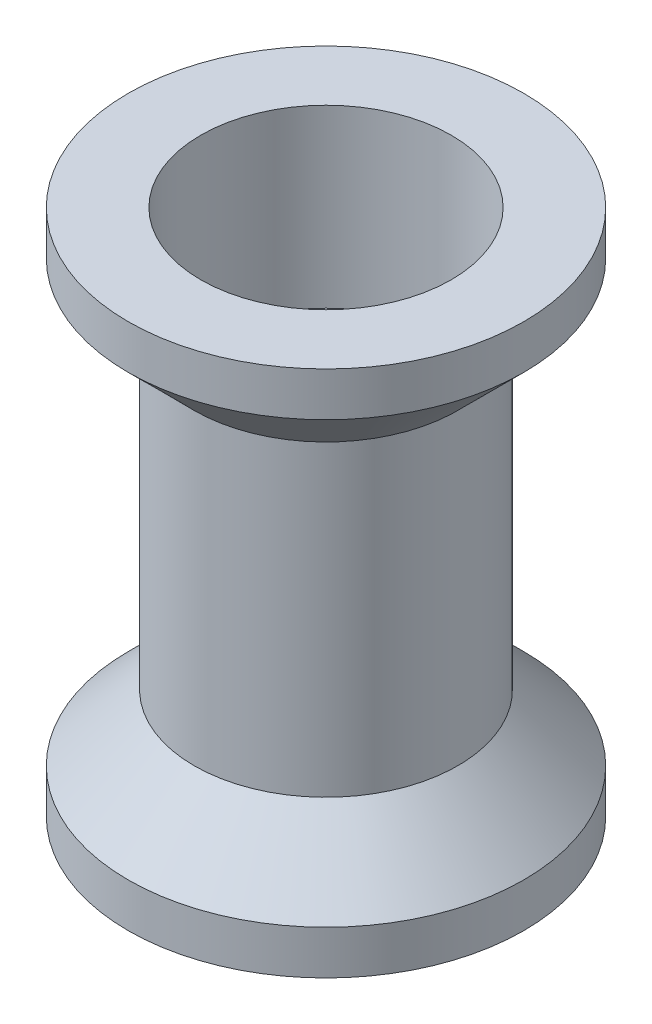
SolidWorks part; units mm, degrees
ref_plane "Front Plane" through (0, 0, 0) normal (0, 0, 1) x (1, 0, 0)
ref_plane "Top Plane" through (0, 0, 0) normal (0, 1, 0) x (1, 0, 0)
ref_plane "Right Plane" through (0, 0, 0) normal (1, 0, 0) x (0, 0, -1)
sketch "Sketch1" plane through (0, 0, 0) normal (0, 1, 0) x (1, 0, 0)
  line L0 (0, 0) -> (0, 2.5) construction
  line L1 (0, 2.5) -> (0, -2.5) construction
  line L2 (0, -2.5) -> (2.5, 0) construction
  line L3 (2.5, 0) -> (-2.5, 0) construction
  line L4 (-2.5, 0) -> (0, 2.5) construction
  line L5 (0, 2.5) -> (2.5, 0) construction
  line L6 (-2.5, 0) -> (0, -2.5) construction
  line L7 (0, 0) -> (-1.7678, 1.7678) construction
  line L8 (-1.7678, 1.7678) -> (-1.7678, -1.7678) construction
  line L9 (-1.7678, -1.7678) -> (1.7678, -1.7678) construction
  line L10 (1.7678, -1.7678) -> (1.7678, 1.7678) construction
  line L11 (1.7678, 1.7678) -> (-1.7678, 1.7678)
  arc A0 (-1.7678, 1.7678) -> (1.7678, 1.7678) centre (0, 0) ccw
  circle A1 centre (0, 0) radius 22.5
  dimension "D1" = 5
  dimension "D2" = 45
  dimension "D3" = 3.5355
extrude "Boss-Extrude1" add sketch "Sketch1" along normal blind 60
sketch "Sketch2" plane through (0, 60, 0) normal (0, 1, 0) x (1, 0, 0)
  circle A0 centre (0, 0) radius 14.25
  dimension "D1" = 28.5
extrude "Cut-Extrude1" cut sketch "Sketch2" against normal blind 20
sketch "Sketch4" plane through (0, 0, 0) normal (0, 0, 1) x (1, 0, 0)
  line L0 (0, 0) -> (22.5, 0) construction
  line L1 (22.5, 0) -> (22.5, 5) construction
  line L2 (22.5, 5) -> (22.5, 55)
  line L3 (22.5, 0) -> (22.5, 60) construction
  line L4 (22.5, 55) -> (15, 55) construction
  line L6 (15, 47.5) -> (22.5, 55)
  line L7 (22.5, 5) -> (15, 5) construction
  line L12 (15, 47.5) -> (15, 12.5)
  line L13 (15, 12.5) -> (22.5, 5)
  dimension "D1" = 50
  dimension "D2" = 35
  dimension "D3" = 10.6066
  dimension "D4" = 7.5
  dimension "D5" = 5
ref_axis "Axis1" through (0, -24.3876, 0) along (0, 1, 0)
revolve "Cut-Revolve3" cut sketch "Sketch4" angle 360 about axis through (0, -24.3876, 0) along (0, 1, 0)
